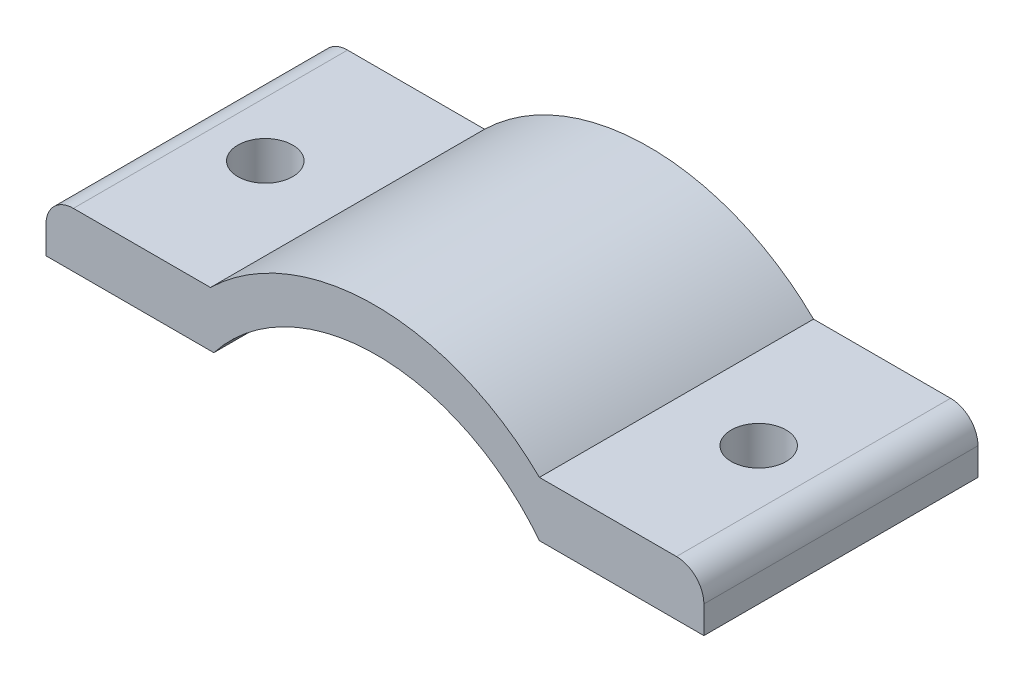
SolidWorks part; units mm, degrees
ref_plane "Front Plane" through (0, 0, 0) normal (0, 0, 1) x (1, 0, 0)
ref_plane "Top Plane" through (0, 0, 0) normal (0, 1, 0) x (1, 0, 0)
ref_plane "Right Plane" through (0, 0, 0) normal (1, 0, 0) x (0, 0, -1)
sketch "Sketch2" plane through (0, 0, 0) normal (0, 0, 1) x (1, 0, 0)
  line L0 (-19.5404, 0) -> (-19.5404, -2)
  line L1 (-19.5404, 0) -> (-13.5404, 0)
  line L2 (-1.5404, 0) -> (4.4596, 0)
  line L3 (-19.5404, -2) -> (-13.4187, -2)
  line L4 (-1.5404, -2) -> (4.4596, -2)
  line L5 (4.4596, -2) -> (4.4596, 0)
  arc A0 (-13.5404, 0) -> (-1.5404, 0) centre (-7.5404, -6.1572) cw
  arc A1 (-13.4187, -2) -> (-1.5404, -2) centre (-7.4795, -6.6317) cw
  point P10 (-7.4795, 0.9)
  dimension "D5" = 2.9
  dimension "D1" = 2
  dimension "D2" = 6
  dimension "D3" = 12
  dimension "D4" = 6
  dimension "D6" = 0
  dimension "D7" = 2
extrude "Boss-Extrude1" add sketch "Sketch2" along normal blind 10
sketch "Sketch3" plane through (0, 0, 0) normal (0, 1, 0) x (1, 0, 0)
  line L0 (-13.5404, 0) -> (-19.5404, 0) construction
  line L2 (-19.5404, -10) -> (-19.5404, 0) construction
  line L4 (4.4596, 0) -> (-1.5404, 0) construction
  circle A0 centre (-16.5404, -5) radius 1
  circle A1 centre (1.4596, -5) radius 1
  point P12 (6.532, -3.1529)
  dimension "D2" = 2
  dimension "D1" = 5
  dimension "D3" = 3
  dimension "D5" = 5
extrude "Cut-Extrude1" cut sketch "Sketch3" against normal blind 10
fillet "Fillet1" radius 1 2 edges at (4.4596, 0, 5) (-19.5404, 0, 5)
